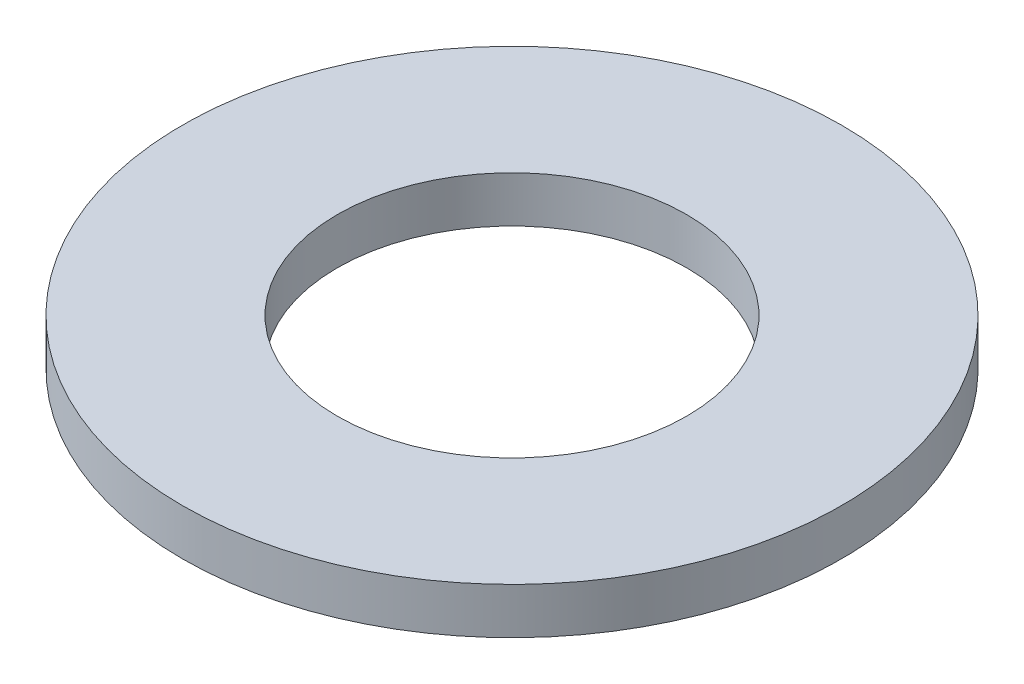
SolidWorks part; units mm, degrees
material "Plain Carbon Steel"
ref_plane "Front Plane" through (0, 0, 0) normal (0, 0, 1) x (1, 0, 0)
ref_plane "Top Plane" through (0, 0, 0) normal (0, 1, 0) x (1, 0, 0)
ref_plane "Right Plane" through (0, 0, 0) normal (1, 0, 0) x (0, 0, -1)
sketch "Sketch1" plane through (0, 0, 0) normal (0, 1, 0) x (1, 0, 0)
  circle A0 centre (0, 0) radius 6.35
  dimension "OD" = 12.7
extrude "Boss-Extrude1" add sketch "Sketch1" along normal blind 0.889
sketch "Sketch5" plane through (0, 0.889, 0) normal (0, 1, 0) x (-1, 0, 0)
  circle A0 centre (0, 0) radius 3.3655
  dimension "ID" = 6.731
extrude "Cut-Extrude1" cut sketch "Sketch5" against normal through all
